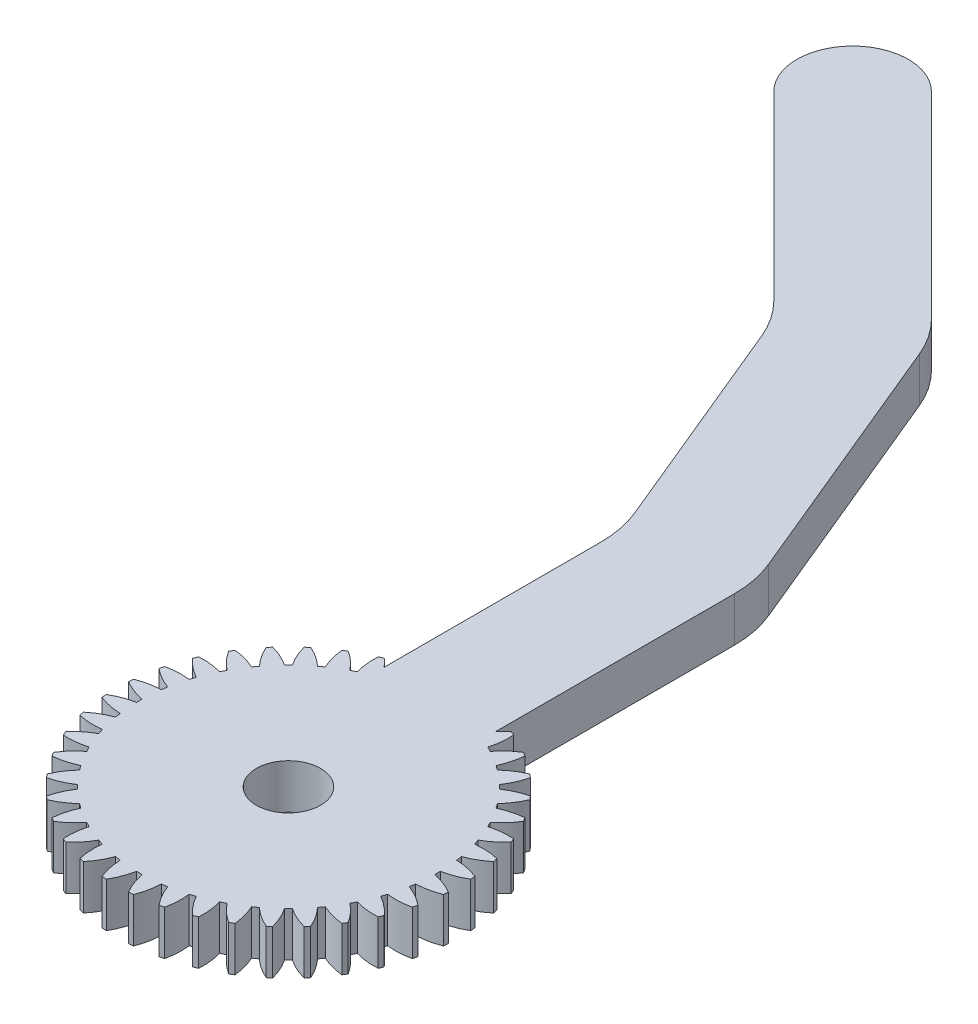
SolidWorks part; units mm, degrees
ref_plane "Front Plane" through (0, 0, 0) normal (0, 0, 1) x (1, 0, 0)
ref_plane "Top Plane" through (0, 0, 0) normal (0, 1, 0) x (1, 0, 0)
ref_plane "Right Plane" through (0, 0, 0) normal (1, 0, 0) x (0, 0, -1)
sketch "Sketch1" plane through (0, 0, 0) normal (0, 1, 0) x (1, 0, 0)
  circle A0 centre (0, 0) radius 15.375
  circle A2 centre (0, 0) radius 2.875
  dimension "D1" = 30.75
  dimension "D3" = 5.75
extrude "Boss-Extrude1" add sketch "Sketch1" along normal blind 4
sketch "Sketch2" plane through (0, 4, 0) normal (0, 1, 0) x (1, 0, 0)
  line L0 (0, 0) -> (0, 15.375) construction
  circle A0 centre (0, 0) radius 13.375
  circle A1 centre (0, 0) radius 15.375 construction
  arc A2 (0.25, 13.3727) -> (1, 15.3424) centre (6.1451, 12.2558) cw
  arc A3 (-0.25, 13.3727) -> (-1, 15.3424) centre (-6.1451, 12.2558) ccw
  circle M3 centre (0, 0) radius 15.375
  dimension "D1" = 2
  dimension "D4" = 6
  dimension "D2" = 0.25
  dimension "D3" = 1
extrude "Cut-Extrude1" cut sketch "Sketch2" along direction (0, 1, 0) on the side against the normal through all contours L0 A0 A2 M3 | A0 L0 A3 M3
pattern_circular "CirPattern1" count 40 over 360 about axis through (0, 0, 0) along (0, 1, 0) of "Cut-Extrude1"
sketch "Sketch3" plane through (0, 4, 0) normal (0, 1, 0) x (1, 0, 0)
  line L5 (5, 10) -> (-5, 10)
  line L6 (0, 0) -> (0, 10) construction
  line L7 (-5, 10) -> (-5, 33.0109)
  line L9 (-5.7612, 36.8377) -> (-13.8059, 56.2593)
  line L10 (-15.9736, 59.5035) -> (-32.2448, 75.7747)
  line L11 (-25.1737, 82.8457) -> (-7.496, 65.1681)
  line L12 (-5.3283, 61.9238) -> (4.2388, 38.8268)
  line L13 (5, 35) -> (5, 10)
  arc A0 (-32.2448, 75.7747) -> (-25.1737, 82.8457) centre (-28.7092, 79.3102) cw
  arc A1 (-5, 33.0109) -> (-5.7612, 36.8377) centre (-15, 33.0109) ccw
  arc A2 (4.2388, 38.8268) -> (5, 35) centre (-5, 35) cw
  arc A3 (-7.496, 65.1681) -> (-5.3283, 61.9238) centre (-14.5671, 58.097) cw
  arc A4 (-13.8059, 56.2593) -> (-15.9736, 59.5035) centre (-23.0447, 52.4324) ccw
  point P16 (-5, 35)
  point P23 (-14.5671, 58.097)
  dimension "D10" = 10
  dimension "D1" = 10
  dimension "D2" = 10
  dimension "D3" = 10
  dimension "D4" = 25
  dimension "D5" = 10
  dimension "D6" = 25
  dimension "D7" = 25
  dimension "D8" = 135
  dimension "D9" = 157.5
extrude "Boss-Extrude2" add sketch "Sketch3" against normal blind 4
